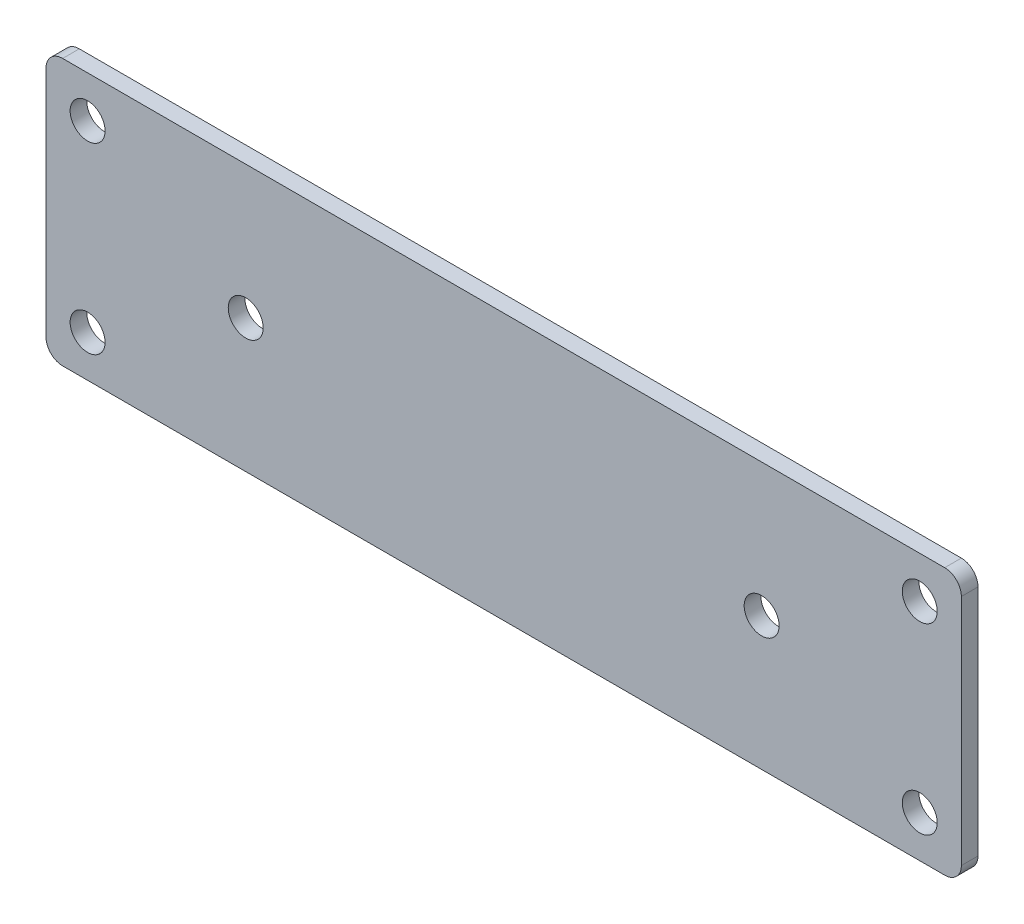
SolidWorks part; units mm, degrees
material "5052-H34"
ref_plane "正面" through (0, 0, 0) normal (0, 0, 1) x (1, 0, 0)
ref_plane "平面" through (0, 0, 0) normal (0, 1, 0) x (1, 0, 0)
ref_plane "右側面" through (0, 0, 0) normal (1, 0, 0) x (0, 0, -1)
sketch "ｽｹｯﾁ1" plane through (0, 0, 0) normal (0, 0, 1) x (1, 0, 0)
  line L0 (0, 0) -> (0, 16) construction
  line L1 (-55, 16) -> (55, 16)
  line L2 (-55, 16) -> (-55, -16)
  line L3 (-55, -16) -> (55, -16)
  line L4 (55, 16) -> (55, -16)
  line L5 (-55, 16) -> (55, -16) construction
  line L6 (-55, -16) -> (55, 16) construction
  line L7 (-50, 11) -> (50, 11) construction
  line L8 (-50, 11) -> (-50, -11) construction
  line L9 (-50, -11) -> (50, -11) construction
  line L10 (50, 11) -> (50, -11) construction
  line L11 (-50, 11) -> (50, -11) construction
  line L12 (-50, -11) -> (50, 11) construction
  line L13 (0, 0) -> (31, 0) construction
  circle A0 centre (31, 0) radius 2.1
  circle A1 centre (-31, 0) radius 2.1
  circle A2 centre (50, 11) radius 2.1
  circle A3 centre (-50, 11) radius 2.1
  circle A4 centre (-50, -11) radius 2.1
  circle A5 centre (50, -11) radius 2.1
  point P0 (0, 0)
  point P6 (0, 0)
  dimension "D5" = 4.2
  dimension "D7" = 4.2
  dimension "D1" = 110
  dimension "D2" = 32
  dimension "D3" = 100
  dimension "D4" = 22
  dimension "D6" = 62
extrude "ﾎﾞｽ - 押し出し1" add sketch "ｽｹｯﾁ1" along normal blind 2
fillet "ﾌｨﾚｯﾄ1" radius 2 4 edges at (-55, -16, 1) (55, -16, 1) (55, 16, 1) (-55, 16, 1)
